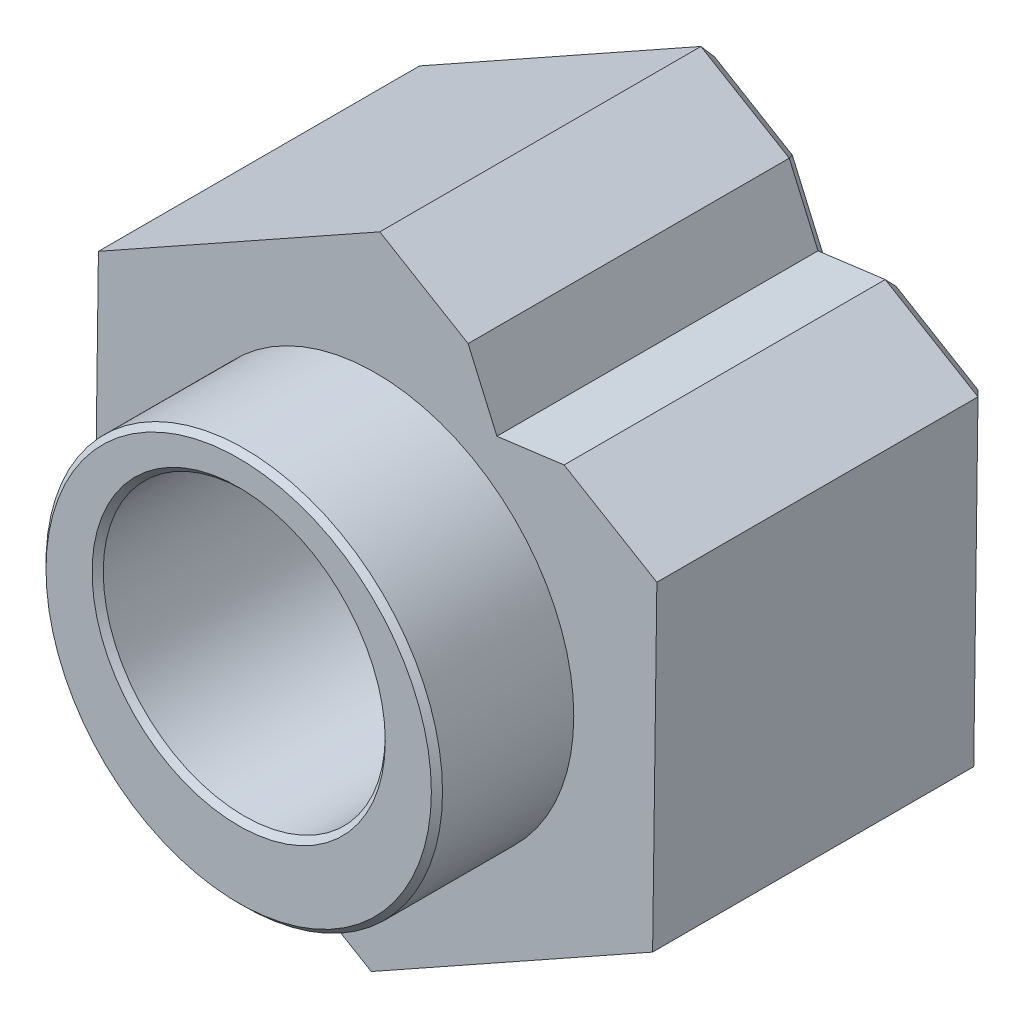
SolidWorks part; units mm, degrees
material "Galvanized Steel"
ref_plane "Plano frontal" through (0, 0, 0) normal (0, 0, 1) x (1, 0, 0)
ref_plane "Plano superior" through (0, 0, 0) normal (0, 1, 0) x (1, 0, 0)
ref_plane "Plano direito" through (0, 0, 0) normal (1, 0, 0) x (0, 0, -1)
sketch "Esboço1" plane through (0, 0, 0) normal (0, 0, 1) x (1, 0, 0)
  line L1 (4.9614, -2.9525) -> (5.0377, 2.8205)
  line L2 (5.0377, 2.8205) -> (0.0762, 5.773)
  line L3 (0.0762, 5.773) -> (-4.9614, 2.9525)
  line L4 (-4.9614, 2.9525) -> (-5.0377, -2.8205)
  line L5 (-5.0377, -2.8205) -> (-0.0762, -5.773)
  line L6 (-0.0762, -5.773) -> (4.9614, -2.9525)
  circle A1 centre (0, 0) radius 5 construction
extrude "Ressalto-extrusão1" add sketch "Esboço1" along normal blind 6
sketch "Esboço2" plane through (0, 0, 6) normal (0, 0, 1) x (1, 0, 0)
  circle A0 centre (0, 0) radius 3.55
  dimension "D1" = 7.1
extrude "Ressalto-extrusão2" add sketch "Esboço2" along normal blind 2.45
sketch "Esboço3" plane through (0, 0, 0) normal (0, 0, -1) x (-1, 0, 0)
  line L0 (0, 0) -> (-2.557, 4.2967) construction
  line L1 (-5.0377, 2.8205) -> (-0.0762, 5.773) construction
  line L2 (-1.658, 4.8317) -> (-2.1734, 3.6522)
  line L3 (-2.1734, 3.6522) -> (-3.3767, 3.8089)
  line L4 (-3.3767, 3.8089) -> (-1.658, 4.8317)
  dimension "D1" = 2
  dimension "D2" = 0.75
extrude "Corte-extrusão1" cut sketch "Esboço3" against normal through all
sketch "Esboço4" plane through (0, 0, 8.45) normal (0, 0, 1) x (1, 0, 0)
  line L0 (0, 2.9) -> (6.6827, 2.9) construction
  line L1 (0, 3.55) -> (-7.4478, 3.55) construction
  circle A0 centre (0, 0.375) radius 2.525
  circle A1 centre (0, 0) radius 3.55 construction
  circle A2 centre (0, 0) radius 3.55 construction
  dimension "D1" = 5.05
  dimension "D2" = 0.65
extrude "Corte-extrusão2" cut sketch "Esboço4" against normal up to next
chamfer "Chanfro2" distance 0.25 angle 45
chamfer "Chanfro3" distance 0.1 angle 45
